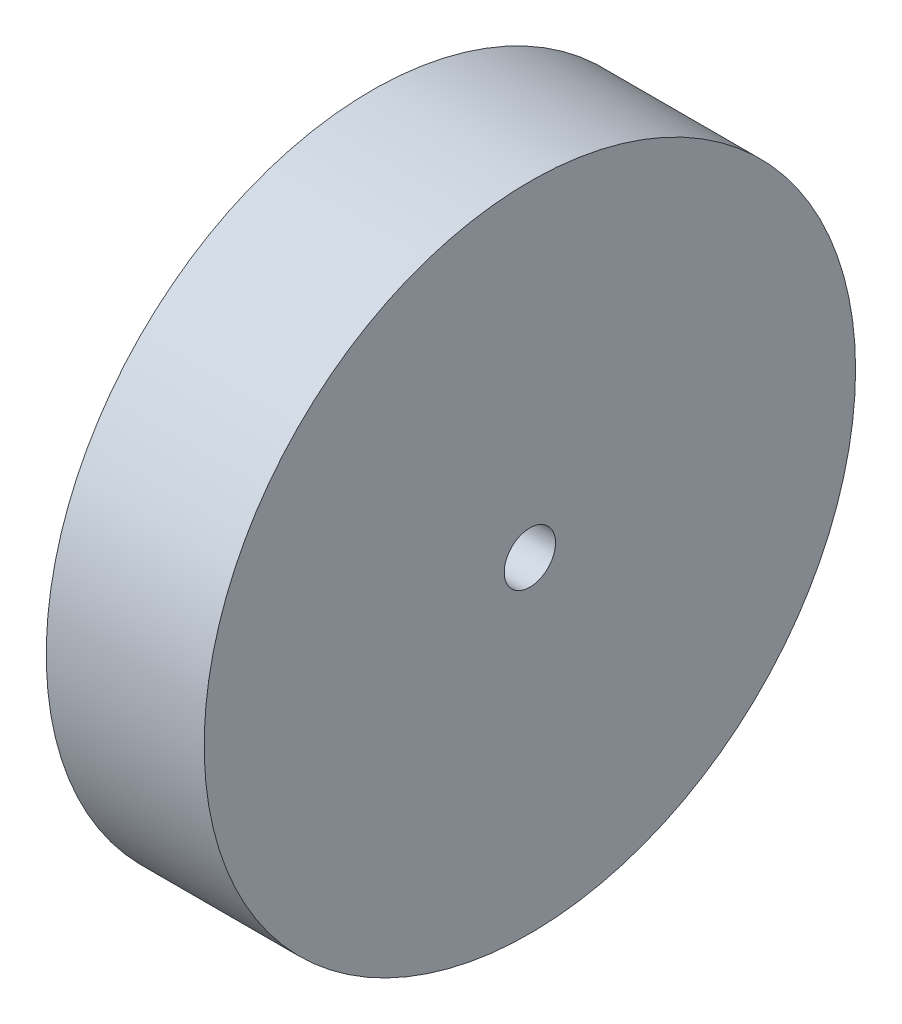
SolidWorks part; units mm, degrees
ref_plane "前视基准面" through (0, 0, 0) normal (0, 0, 1) x (1, 0, 0)
ref_plane "上视基准面" through (0, 0, 0) normal (0, 1, 0) x (1, 0, 0)
ref_plane "右视基准面" through (0, 0, 0) normal (1, 0, 0) x (0, 0, -1)
other "Configuration Table"
sketch "草图1" plane through (0, 0, 0) normal (1, 0, 0) x (0, 0, -1)
  circle A0 centre (0, 0) radius 33
  dimension "D1" = 66
extrude "凸台-拉伸1" add sketch "草图1" along normal blind 16
sketch "草图2" plane through (16, 0, 0) normal (1, 0, 0) x (0, 0, -1)
  circle A0 centre (0, 0) radius 2.6
  dimension "D1" = 5.2
extrude "切除-拉伸1" cut sketch "草图2" against normal blind 16
